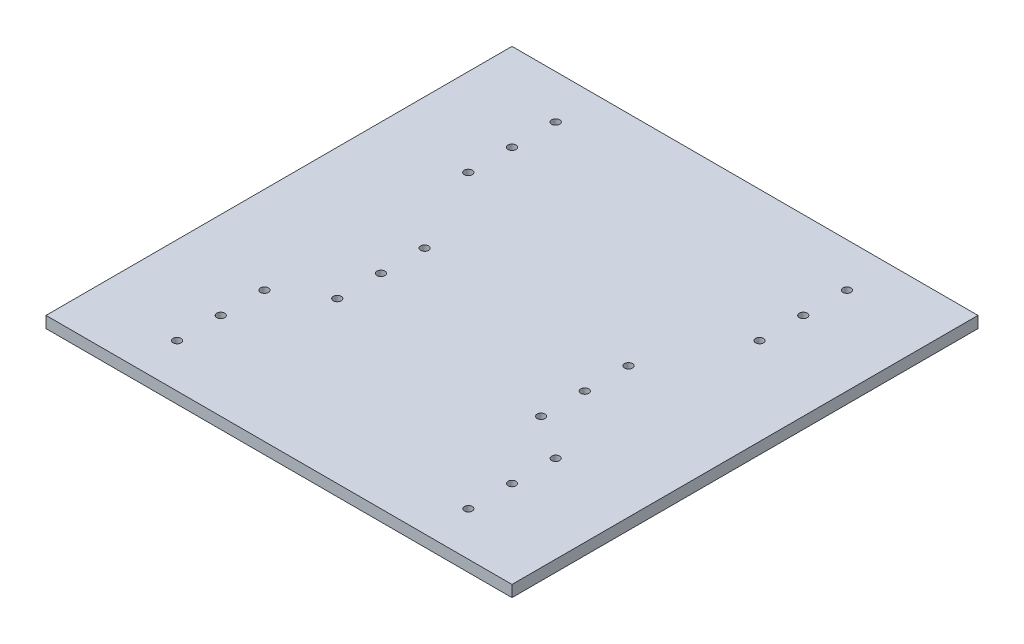
SolidWorks part; units mm, degrees
ref_plane "Front Plane" through (0, 0, 0) normal (0, 0, 1) x (1, 0, 0)
ref_plane "Top Plane" through (0, 0, 0) normal (0, 1, 0) x (1, 0, 0)
ref_plane "Right Plane" through (0, 0, 0) normal (1, 0, 0) x (0, 0, -1)
sketch "Sketch2" plane through (0, 0, 0) normal (0, 1, 0) x (1, 0, 0)
  line L1 (-101.6, -101.6) -> (101.6, -101.6)
  line L2 (-101.6, -101.6) -> (-101.6, 101.6)
  line L3 (-101.6, 101.6) -> (101.6, 101.6)
  line L4 (101.6, -101.6) -> (101.6, 101.6)
  line L5 (-101.6, -101.6) -> (101.6, 101.6) construction
  line L6 (-101.6, 101.6) -> (101.6, -101.6) construction
  point P0 (0, 0)
  dimension "D1" = 203.2
  dimension "D2" = 203.2
extrude "Base" add sketch "Sketch2" along normal blind 5
hole_wizard "Tap Drill for #8-32 Tap1" positions "Sketch4" profile "Sketch3" hole size "#8-32" standard "ANSI Inch" end condition up to next
sketch "Sketch4" plane through (0, 5, 0) normal (0, 1, 0) x (1, 0, 0)
  point P0 (-44.45, 6.35)
  point P3 (-44.45, -12.7)
  point P6 (-44.45, -31.75)
  point P9 (44.45, -31.75)
  point P12 (44.45, -12.7)
  point P14 (44.45, 6.35)
  point P17 (-63.5, -44.45)
  point P20 (-63.5, -63.5)
  point P23 (-63.5, -82.55)
  point P30 (63.5, -44.45)
  point P34 (63.5, -82.55)
  point P37 (63.5, -63.5)
  point P38 (63.5, 82.55)
  point P41 (63.5, 63.5)
  point P44 (63.5, 44.45)
  point P47 (-63.5, 44.45)
  point P50 (-63.5, 63.5)
  point P52 (-63.5, 82.55)
sketch "Sketch3" plane through (-44.45, 5, -6.35) normal (1, 0, 0) x (0, 0, 1)
  line L0 (0, 0) -> (0, 5)
  line L1 (0, 5) -> (1.7272, 5)
  line L2 (1.7272, 5) -> (1.7272, 0)
  line L5 (1.7272, 0) -> (0, 0)
  line L11 (0, -6.35) -> (0, 107.95) construction
  dimension "Thru Hole Dia." = 3.4544
  dimension "Thru Hole Depth" = 5
equation "\"width\"=8"
equation "\"D1@Sketch2\"=\"width\""
equation "\"gauge3\"=10"
equation "\"gauge5\"=0.19685"
equation "\"D1@Base\"=\"gauge5\""
